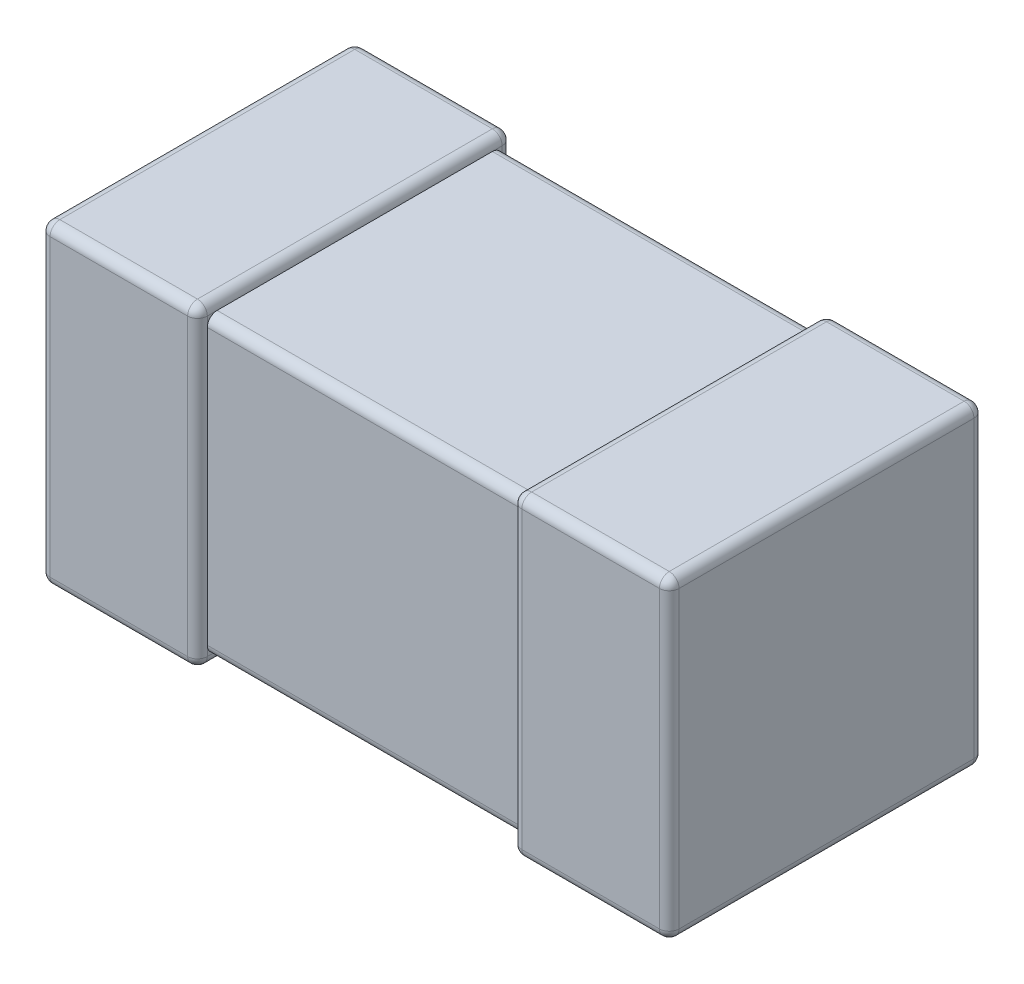
SolidWorks part; units mm, degrees
ref_plane "Front Plane" through (0, 0, 0) normal (0, 0, 1) x (1, 0, 0)
ref_plane "Top Plane" through (0, 0, 0) normal (0, 1, 0) x (1, 0, 0)
ref_plane "Right Plane" through (0, 0, 0) normal (1, 0, 0) x (0, 0, -1)
ref_plane "Plane4" through (0, 0.05, 0) normal (0, 1, 0) x (1, 0, 0)
sketch "Sketch1" plane through (0, 0.05, 0) normal (0, 1, 0) x (1, 0, 0)
  line L1 (-1.55, 0.75) -> (1.55, 0.75)
  line L2 (-1.55, 0.75) -> (-1.55, -0.75)
  line L3 (-1.55, -0.75) -> (1.55, -0.75)
  line L4 (1.55, 0.75) -> (1.55, -0.75)
  dimension "D1" = 3.1
  dimension "D2" = 1.55
  dimension "D3" = 1.5
  dimension "D4" = 0.75
extrude "Boss-Extrude1" add sketch "Sketch1" along normal blind 1.5
sketch "Sketch2" plane through (0, 0, 0) normal (0, 1, 0) x (1, 0, 0)
  line L0 (-1.55, 0.75) -> (-1.55, -0.75) construction
  line L1 (-1.6, 0.8) -> (-0.8, 0.8)
  line L2 (-1.6, 0.8) -> (-1.6, -0.8)
  line L3 (-1.6, -0.8) -> (-0.8, -0.8)
  line L4 (-0.8, 0.8) -> (-0.8, -0.8)
  line L5 (0.8, 0.8) -> (1.6, 0.8)
  line L6 (0.8, 0.8) -> (0.8, -0.8)
  line L7 (0.8, -0.8) -> (1.6, -0.8)
  line L8 (1.6, 0.8) -> (1.6, -0.8)
  line L9 (1.55, -0.75) -> (1.55, 0.75) construction
  line L10 (-1.55, -0.75) -> (1.55, -0.75) construction
  line L11 (1.55, 0.75) -> (-1.55, 0.75) construction
  dimension "D1" = 0.05
  dimension "D2" = 0.05
  dimension "D3" = 0.8
  dimension "D4" = 0.8
  dimension "D5" = 0.05
  dimension "D6" = 0.05
extrude "Boss-Extrude2" add sketch "Sketch2" along normal offset from surface (1.6 mm away) 0.05 separate body up to face at (0, 1.55, 0) offset beyond the face yes
fillet "Fillet1" radius 0.05 12 edges at (0.8, 0, 0) (1.2, 0, 0.8) (0.8, 0.8, 0.8) (1.6, 0, 0) (1.6, 0.8, 0.8) (0.8, 0.8, -0.8) (1.2, 0, -0.8) (1.6, 0.8, -0.8) (1.6, 1.6, 0) (1.2, 1.6, 0.8) (0.8, 1.6, 0) (1.2, 1.6, -0.8)
fillet "Fillet2" radius 0.05 12 edges at (-0.8, 0.8, -0.8) (-0.8, 0, 0) (-1.2, 0, -0.8) (-1.6, 0, 0) (-1.6, 0.8, -0.8) (-0.8, 0.8, 0.8) (-1.2, 0, 0.8) (-1.6, 0.8, 0.8) (-0.8, 1.6, 0) (-1.2, 1.6, 0.8) (-1.6, 1.6, 0) (-1.2, 1.6, -0.8)
fillet "Fillet3" radius 0.05 12 edges at (1.55, 0.05, 0) (-1.55, 0.05, 0) (1.55, 0.8, -0.75) (-1.55, 0.8, -0.75) (0, 0.05, -0.75) (-1.55, 0.8, 0.75) (1.55, 0.8, 0.75) (0, 0.05, 0.75) (0, 1.55, -0.75) (1.55, 1.55, 0) (0, 1.55, 0.75) (-1.55, 1.55, 0)
equation "\"D2@Sketch1\"=\"D1@Sketch1\"/2"
equation "\"D4@Sketch1\"=\"D3@Sketch1\"/2"
equation "\"D6@Sketch2\"=\"D5@Sketch2\""
